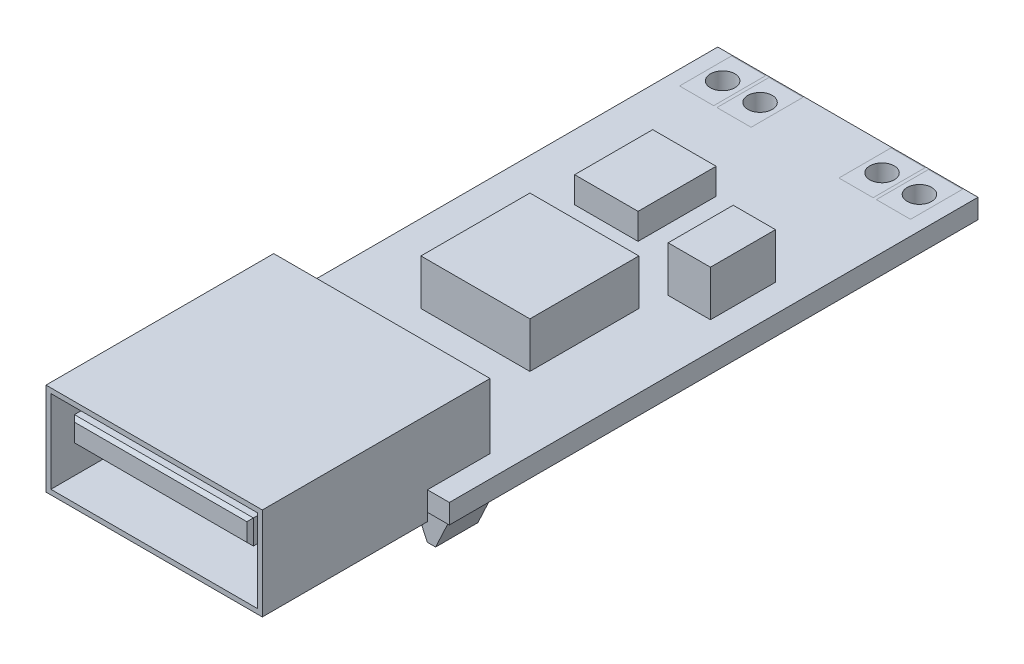
SolidWorks part; units mm, degrees
material "C-Fibra di vetro"
ref_plane "Piano Frontale" through (0, 0, 0) normal (0, 0, 1) x (1, 0, 0)
ref_plane "Piano Superiore" through (0, 0, 0) normal (0, 1, 0) x (1, 0, 0)
ref_plane "Piano Destro" through (0, 0, 0) normal (1, 0, 0) x (0, 0, -1)
sketch "Schizzo1" plane through (0, 0, 0) normal (0, 1, 0) x (1, 0, 0)
  line L1 (8, -16.25) -> (-8, -16.25)
  line L2 (8, -16.25) -> (8, 16.25)
  line L3 (8, 16.25) -> (-8, 16.25)
  line L4 (-8, -16.25) -> (-8, 16.25)
  line L5 (8, -16.25) -> (-8, 16.25) construction
  line L6 (8, 16.25) -> (-8, -16.25) construction
  point P0 (0, 0)
  dimension "D1" = 16
  dimension "D2" = 32.5
extrude "Estrusione-Estrusione1" add sketch "Schizzo1" along normal blind 1.2
sketch "Schizzo3" plane through (0, 0, 0) normal (1, 0, 0) x (0, 0, -1)
  line L0 (-26.4, -0.5) -> (-26.4, 5.2)
  line L1 (-26.4, 5.2) -> (-12.4, 5.2)
  line L2 (-12.4, 5.2) -> (-12.4, 1.2)
  line L3 (-16.25, 1.2) -> (16.25, 1.2) construction
  line L4 (-12.4, 1.2) -> (-16.25, 1.2)
  line L5 (-16.25, 1.2) -> (-16.25, -0.5)
  line L6 (-16.25, -0.5) -> (-26.4, -0.5)
  line L7 (16.25, 1.2) -> (16.25, 0) construction
  dimension "D1" = 5.7
  dimension "D2" = 4
  dimension "D3" = 42.65
  dimension "D4" = 14
extrude "Estrusione-Estrusione2" add sketch "Schizzo3" along normal mid plane 13.3 separate body
shell "Svuota1" thickness 0.3
sketch "Schizzo4" plane through (0, 0, 12.7) normal (0, 0, 1) x (1, 0, 0)
  line L0 (6.35, 4.9) -> (-6.35, 4.9) construction
  line L1 (5.5, 2.4) -> (-5.5, 2.4)
  line L2 (5.5, 2.4) -> (5.5, 3.9)
  line L3 (5.5, 3.9) -> (-5.5, 3.9)
  line L4 (-5.5, 2.4) -> (-5.5, 3.9)
  line L5 (5.5, 2.4) -> (-5.5, 3.9) construction
  line L6 (5.5, 3.9) -> (-5.5, 2.4) construction
  point P0 (0, 3.15)
  dimension "D1" = 11
  dimension "D2" = 1.5
  dimension "D3" = 1
extrude "Estrusione-Estrusione3" add sketch "Schizzo4" along normal blind 13.3
chamfer "Smusso1" distance 0.2 angle 45 4 edges at (0, 3.9, 26) (5.5, 3.15, 26) (0, 2.4, 26) (-5.5, 3.15, 26)
sketch "Schizzo5" plane through (0, 0, 0) normal (0, -1, 0) x (1, 0, 0)
  line L0 (0, 0) -> (0, 16.25) construction
  line L1 (-7.5, 15.85) -> (-5.5, 15.85)
  line L2 (-7.5, 15.85) -> (-7.5, 13.25)
  line L3 (-7.5, 13.25) -> (-5.5, 13.25)
  line L4 (-5.5, 15.85) -> (-5.5, 13.25)
  line L5 (-7.5, 15.85) -> (-5.5, 13.25) construction
  line L6 (-7.5, 13.25) -> (-5.5, 15.85) construction
  line L7 (-8, 16.25) -> (8, 16.25) construction
  line L8 (7.5, 15.85) -> (5.5, 15.85)
  line L9 (7.5, 15.85) -> (7.5, 13.25)
  line L10 (7.5, 13.25) -> (5.5, 13.25)
  line L11 (5.5, 15.85) -> (5.5, 13.25)
  line L12 (8, -16.25) -> (-8, -16.25) construction
  point P0 (-6.5, 14.55)
  dimension "D1" = 2.6
  dimension "D2" = 2
  dimension "D3" = 11
  dimension "D4" = 29.5
extrude "Estrusione-Estrusione4" add sketch "Schizzo5" along normal blind 2
chamfer "Smusso2" distance 1.6 angle 25 4 edges at (-7.5, -2, 14.55) (-5.5, -2, 14.55) (5.5, -2, 14.55) (7.5, -2, 14.55)
sketch "Schizzo6" plane through (0, 1.2, 0) normal (0, 1, 0) x (1, 0, 0)
  line L0 (6.65, -12.4) -> (-6.65, -12.4) construction
  line L1 (-3.2, -0.1) -> (3.5, -0.1)
  line L2 (-3.2, -0.1) -> (-3.2, -6.8)
  line L3 (-3.2, -6.8) -> (3.5, -6.8)
  line L4 (3.5, -0.1) -> (3.5, -6.8)
  line L5 (-3.2, -0.1) -> (3.5, -6.8) construction
  line L6 (-3.2, -6.8) -> (3.5, -0.1) construction
  line L7 (6.3, 1.5) -> (3.7, 1.5)
  line L8 (6.3, 1.5) -> (6.3, 5.5)
  line L9 (6.3, 5.5) -> (3.7, 5.5)
  line L10 (3.7, 1.5) -> (3.7, 5.5)
  line L11 (6.3, 1.5) -> (3.7, 5.5) construction
  line L12 (6.3, 5.5) -> (3.7, 1.5) construction
  line L13 (8, -16.25) -> (8, 16.25) construction
  line L14 (8, 16.25) -> (-8, 16.25) construction
  point P0 (0.15, -3.45)
  point P5 (5, 3.5)
  dimension "D1" = 6.7
  dimension "D2" = 6.7
  dimension "D3" = 5.6
  dimension "D4" = 4.5
  dimension "D5" = 1.7
  dimension "D6" = 4
  dimension "D7" = 2.6
  dimension "D8" = 10.75
extrude "Estrusione-Estrusione5" add sketch "Schizzo6" along normal blind 2.8
sketch "Schizzo7" plane through (0, 1.2, 0) normal (0, 1, 0) x (1, 0, 0)
  line L0 (8, 16.25) -> (-8, 16.25) construction
  line L1 (-0.1, 3.45) -> (-4, 3.45)
  line L2 (-0.1, 3.45) -> (-0.1, 8.25)
  line L3 (-0.1, 8.25) -> (-4, 8.25)
  line L4 (-4, 3.45) -> (-4, 8.25)
  line L5 (-0.1, 3.45) -> (-4, 8.25) construction
  line L6 (-0.1, 8.25) -> (-4, 3.45) construction
  line L7 (-8, 16.25) -> (-8, -16.25) construction
  point P0 (-2.05, 5.85)
  dimension "D1" = 3.9
  dimension "D2" = 4.8
  dimension "D3" = 8
  dimension "D4" = 4
extrude "Estrusione-Estrusione6" add sketch "Schizzo7" along normal blind 1.6
sketch "Schizzo9" plane through (0, 1.2, 0) normal (0, 1, 0) x (1, 0, 0)
  line L0 (0, 0) -> (0, 16.25) construction
  line L1 (8, 16.25) -> (-8, 16.25) construction
  circle A0 centre (-6.05, 14.6) radius 0.75
  circle A1 centre (-3.75, 14.6) radius 0.75
  circle A2 centre (3.75, 14.6) radius 0.75
  circle A3 centre (6.05, 14.6) radius 0.75
  dimension "D1" = 1.5
  dimension "D2" = 2.3
  dimension "D3" = 7.5
  dimension "D4" = 1.65
extrude "Taglio-Estrusione1" cut sketch "Schizzo9" against normal through all
sketch "Schizzo10" plane through (0, 1.2, 0) normal (0, 1, 0) x (1, 0, 0)
  line L1 (-7.1, 16.2) -> (-5, 16.2)
  line L2 (-7.1, 16.2) -> (-7.1, 13)
  line L3 (-7.1, 13) -> (-5, 13)
  line L4 (-5, 16.2) -> (-5, 13)
  line L5 (-7.1, 16.2) -> (-5, 13) construction
  line L6 (-7.1, 13) -> (-5, 16.2) construction
  line L7 (-4.8, 16.2) -> (-2.7, 16.2)
  line L8 (-4.8, 16.2) -> (-4.8, 13)
  line L9 (-4.8, 13) -> (-2.7, 13)
  line L10 (-2.7, 16.2) -> (-2.7, 13)
  line L11 (-4.8, 16.2) -> (-2.7, 13) construction
  line L12 (-4.8, 13) -> (-2.7, 16.2) construction
  line L13 (2.7, 16.2) -> (4.8, 16.2)
  line L14 (2.7, 16.2) -> (2.7, 13)
  line L15 (2.7, 13) -> (4.8, 13)
  line L16 (4.8, 16.2) -> (4.8, 13)
  line L17 (2.7, 16.2) -> (4.8, 13) construction
  line L18 (2.7, 13) -> (4.8, 16.2) construction
  line L19 (5, 16.2) -> (7.1, 16.2)
  line L20 (5, 16.2) -> (5, 13)
  line L21 (5, 13) -> (7.1, 13)
  line L22 (7.1, 16.2) -> (7.1, 13)
  line L23 (5, 16.2) -> (7.1, 13) construction
  line L24 (5, 13) -> (7.1, 16.2) construction
  point P0 (-6.05, 14.6)
  point P6 (-3.75, 14.6)
  point P12 (3.75, 14.6)
  point P18 (6.05, 14.6)
  dimension "D1" = 2.1
  dimension "D2" = 3.2
split line "Linea di divisione1"
sketch "Schizzo11" plane through (0, 0, 0) normal (0, -1, 0) x (1, 0, 0)
  line L0 (-7.1, -13) -> (-2.7, -13) construction
  line L1 (2.7, -13) -> (7.1, -13) construction
  text T0 "IN+" font "Century Gothic" height in points 5
  text T1 "IN-" font "Century Gothic" height in points 5
split line "Linea di divisione2"
